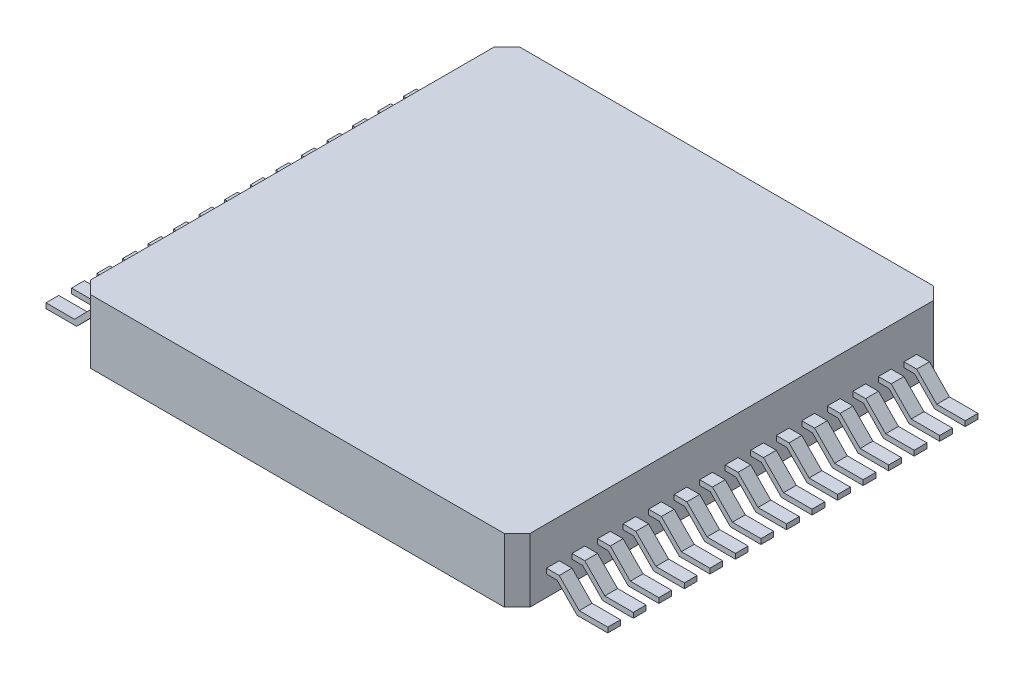
SolidWorks part; units mm, degrees
ref_plane "Alzado" through (0, 0, 0) normal (0, 0, 1) x (1, 0, 0)
ref_plane "Planta" through (0, 0, 0) normal (0, 1, 0) x (1, 0, 0)
ref_plane "Vista lateral" through (0, 0, 0) normal (1, 0, 0) x (0, 0, -1)
sketch "Croquis1" plane through (0, 0, 0) normal (0, 1, 0) x (1, 0, 0)
  line L0 (-8.1, 8.4) -> (-8.6, 7.9)
  line L1 (8.1, -8.4) -> (-8.1, -8.4)
  line L2 (8.6, -7.9) -> (8.6, 7.9)
  line L3 (8.1, 8.4) -> (-8.1, 8.4)
  line L4 (-8.6, -7.9) -> (-8.6, 7.9)
  line L5 (8.6, -8.4) -> (-8.6, 8.4) construction
  line L6 (8.6, 8.4) -> (-8.6, -8.4) construction
  line L7 (-8.1, -8.4) -> (-8.6, -7.9)
  line L8 (8.6, -7.9) -> (8.1, -8.4)
  line L9 (8.6, 7.9) -> (8.1, 8.4)
  point P0 (0, 0)
  dimension "D1" = 17.2
  dimension "D2" = 16.8
extrude "Saliente-Extruir1" add sketch "Croquis1" along normal blind 2.5
ref_plane "Plano1" through (0, 0, 7.25) normal (0, 0, 1) x (1, 0, 0)
sketch "Croquis2" plane through (0, 0, 7.25) normal (0, 0, 1) x (1, 0, 0)
  line L0 (8.6, 0.8) -> (9.016, 0.8)
  line L1 (8.6, 2.5) -> (8.6, 0) construction
  line L2 (9.016, 0.8) -> (9.8, 0)
  line L3 (9.8, 0) -> (11, 0)
  line L4 (11, 0) -> (11, 0.2)
  line L5 (11, 0.2) -> (9.884, 0.2)
  line L6 (9.884, 0.2) -> (9.1, 1)
  line L7 (9.1, 1) -> (8.6, 1)
  line L8 (8.6, 1) -> (8.6, 0.8)
  line L9 (8.6, 0) -> (8.1, 0) construction
  line L10 (0, 0) -> (0, 2.5) construction
  line L11 (-8.1, 2.5) -> (8.1, 2.5) construction
  line L12 (-11, 0) -> (-11, 0.2)
  line L13 (-9.8, 0) -> (-11, 0)
  line L14 (-11, 0.2) -> (-9.884, 0.2)
  line L15 (-9.016, 0.8) -> (-9.8, 0)
  line L16 (-9.884, 0.2) -> (-9.1, 1)
  line L17 (-9.1, 1) -> (-8.6, 1)
  line L18 (-8.6, 1) -> (-8.6, 0.8)
  line L19 (-8.6, 0.8) -> (-9.016, 0.8)
  dimension "D1" = 0.2
  dimension "D2" = 0.2
  dimension "D3" = 2.4
  dimension "D4" = 0.2
  dimension "D5" = 0.5
  dimension "D6" = 1
  dimension "D7" = 1.2
extrude "Saliente-Extruir2" add sketch "Croquis2" against normal blind 0.5
pattern_linear "MatrizL1" count 15 spacing 1 along (0, 0, -1) of "Saliente-Extruir2"
